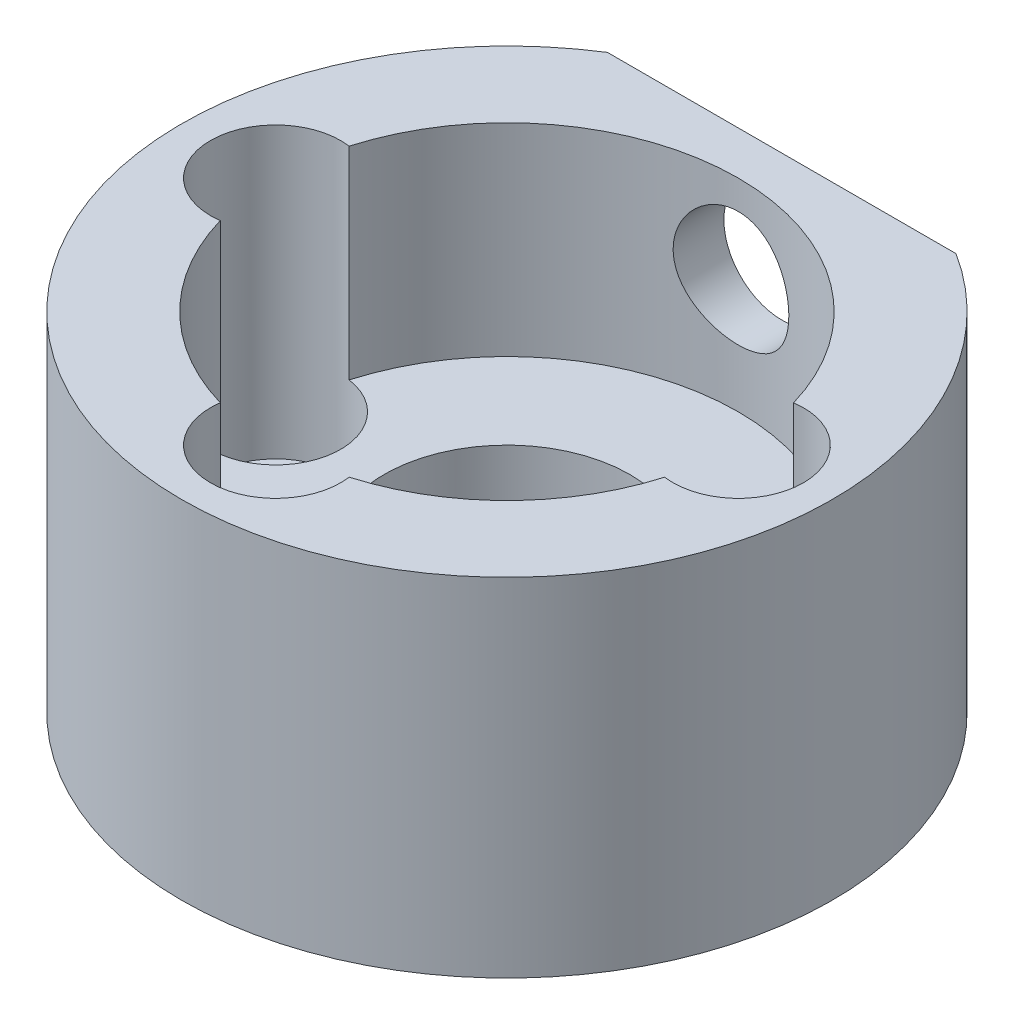
SolidWorks part; units mm, degrees
ref_plane "Plan de face" through (0, 0, 0) normal (0, 0, 1) x (1, 0, 0)
ref_plane "Plan de dessus" through (0, 0, 0) normal (0, 1, 0) x (1, 0, 0)
ref_plane "Plan de droite" through (0, 0, 0) normal (1, 0, 0) x (0, 0, -1)
sketch "Esquisse1" plane through (0, 0, 0) normal (0, 1, 0) x (1, 0, 0)
  line L4 (6.026, 9.5) -> (-6.026, 9.5)
  arc A0 (-6.026, 9.5) -> (6.026, 9.5) centre (0, 0) ccw
  dimension "D1" = 22.5
  dimension "D4" = 9.5
extrude "Boss.-Extru.1" add sketch "Esquisse1" along normal blind 12
hole_wizard "Chambrage pour vis à tête cylindrique à 6 pans creux (ou vis CHC) M21" positions "Esquisse8" profile "Esquisse9" counterbore size "M2" standard "Ansi Metric" end condition through all
sketch "Esquisse8" plane through (0, 12, 0) normal (0, 1, 0) x (1, 0, 0)
  line L0 (0, 0) -> (8, 0) construction
  line L2 (0, 0) -> (0, -8) construction
  line L4 (0, 0) -> (-8, 0) construction
  point P0 (8, 0)
  point P2 (0, -8)
  point P4 (-8, 0)
  dimension "D1" = 8
sketch "Esquisse9" plane through (8, 12, 0) normal (1, 0, 0) x (0, 0, 1)
  line L0 (0, 0) -> (0, 12)
  line L1 (0, 12) -> (1.25, 12)
  line L3 (1.25, 12) -> (1.25, 10)
  line L4 (1.25, 10) -> (2.25, 10)
  line L5 (2.25, 10) -> (2.25, 0)
  line L7 (2.25, 0) -> (0, 0)
  line L11 (0, -6.35) -> (0, 107.95) construction
  dimension "Diamètre du perçage jusqu'au prochain" = 2.5
  dimension "Profondeur du perçage jusqu'au prochain" = 12
  dimension "Diamètre du chambrage" = 4.5
  dimension "Profondeur du chambrage" = 10
sketch "Esquisse12" plane through (0, 12, 0) normal (0, 1, 0) x (1, 0, 0)
  circle A0 centre (0, 0) radius 8
  dimension "D1" = 16
extrude "Enlèv. mat.-Extru.1" cut sketch "Esquisse12" against normal blind 7
sketch "Esquisse14" plane through (0, 0, -9.5) normal (0, 0, -1) x (-1, 0, 0)
  line L1 (-6.026, 12) -> (6.026, 12) construction
  circle A0 centre (0, 9) radius 2
  dimension "D1" = 3
extrude "Enlèv. mat.-Extru.2" cut sketch "Esquisse14" against normal blind 10
sketch "Esquisse15" plane through (0, 0, 0) normal (0, -1, 0) x (1, 0, 0)
  circle A0 centre (0, 0) radius 4.25
  dimension "D1" = 8.5
extrude "Enlèv. mat.-Extru.3" cut sketch "Esquisse15" against normal through all
